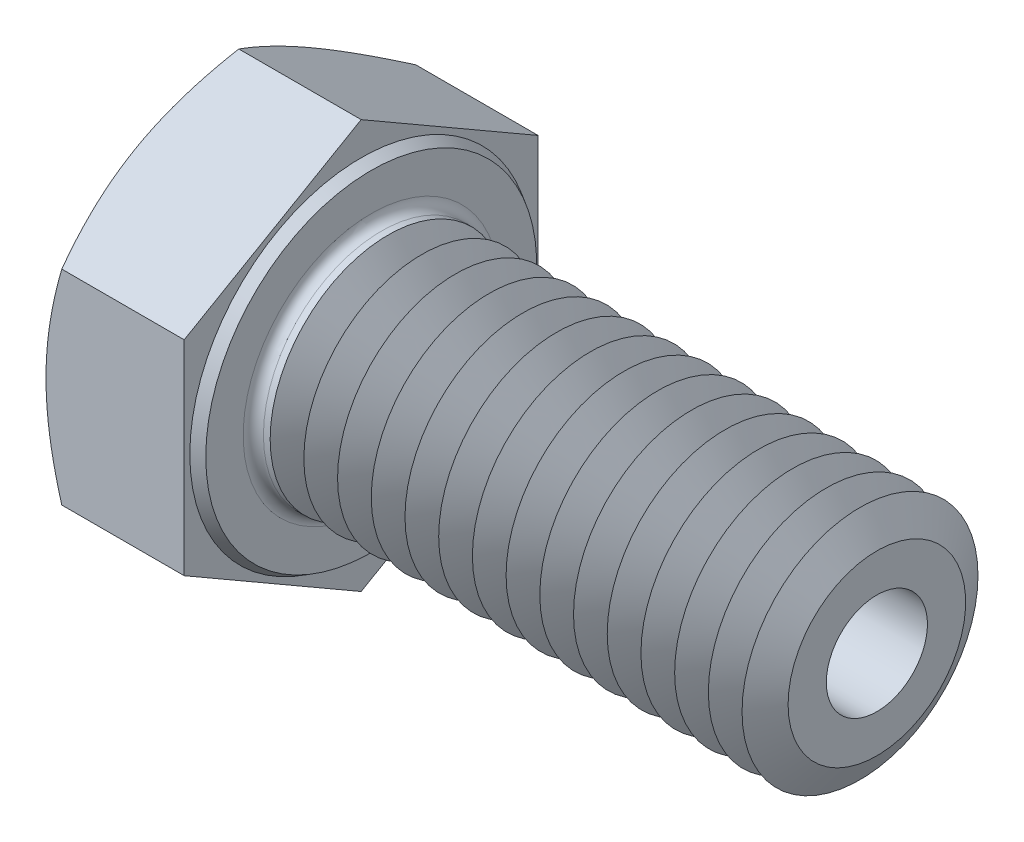
SolidWorks part; units mm, degrees
material "45"
ref_plane "前视" through (0, 0, 0) normal (0, 0, 1) x (1, 0, 0)
ref_plane "上视" through (0, 0, 0) normal (0, 1, 0) x (1, 0, 0)
ref_plane "右视" through (0, 0, 0) normal (1, 0, 0) x (0, 0, -1)
sketch "草图1" plane through (0, 0, 0) normal (1, 0, 0) x (0, 0, -1)
  line L0 (10.5, 6.0622) -> (10.5, -6.0622)
  line L1 (-10.5, 6.0622) -> (-10.5, -6.0622)
  line L2 (10.5, -6.0622) -> (0, -12.1244)
  line L3 (0, -12.1244) -> (-10.5, -6.0622)
  line L4 (10.5, 6.0622) -> (0, 12.1244)
  line L5 (0, 12.1244) -> (-10.5, 6.0622)
  circle A0 centre (0, 0) radius 11.68 construction
  dimension "e" = 23.36
  dimension "s" = 21
  dimension "D2" = 120
  dimension "D3" = 10.5
  dimension "D4" = 10.5
  dimension "D5" = 10.5
extrude "基体-拉伸" add sketch "草图1" along normal blind 8.8
sketch "草图2" plane through (0, 0, 0) normal (0, 0, 1) x (1, 0, 0)
  line L0 (0, 6.0622) -> (0, -6.0622) construction
  line L1 (0, 0) -> (38.8, 0)
  line L2 (0, 0) -> (0, 7)
  line L3 (0, 7) -> (38.8, 7)
  line L4 (38.8, 0) -> (38.8, 5.268)
  line L5 (8.8, 12.1244) -> (8.8, 6.0622) construction
  line L6 (0, 0) -> (-15.7, 0) construction
  line L7 (0, 0) -> (19.4, 0) construction
  line L8 (38.8, -5.268) -> (90.335, -7) construction
  line L9 (0, -7) -> (90.335, -7) construction
  line L10 (10.8, 7) -> (10.8, 0) construction
  line L11 (8.8, 13.0554) -> (8.8, -1.27) construction
  line L12 (8.8, 6.0622) -> (8.8, -6.0622) construction
  line L14 (38.8, 7) -> (38.8, 5.268)
  dimension "l" = 30
  dimension "d" = 14
  dimension "Minor_dia" = 10.536
  dimension "p" = 2
  dimension "b" = 30
  dimension "da" = 15.7
revolve "凸台-旋转1" add sketch "草图2" angle 360 about L7
cosmetic thread "螺旋线1" parameters "Thread_length"=27, "Thread_minor"=10.536
sketch "草图3" plane through (0, 0, 0) normal (0, 0, 1) x (1, 0, 0)
  line L0 (0, 10.5) -> (3.8246, 17.1244)
  line L1 (0, 12.1244) -> (0, 6.0622) construction
  line L2 (3.8246, 17.1244) -> (3.8246, 22.1244)
  line L3 (3.8246, 22.1244) -> (-10, 22.1244)
  line L4 (-10, 22.1244) -> (-10, 10.5)
  line L5 (-10, 10.5) -> (0, 10.5)
  line L6 (0, 0) -> (99.06, 0) construction
  line L7 (8.8, 12.1244) -> (0, 12.1244) construction
  dimension "D1" = 10.5
  dimension "D2" = 5
  dimension "D3" = 10
  dimension "D4" = 5
  dimension "Head_ch_ang" = 30
revolve "切除-旋转1" cut sketch "草图3" angle 360 about L6
sketch "草图4" plane through (0, 0, 0) normal (0, 0, 1) x (1, 0, 0)
  line L0 (0, 0) -> (248.9073, 0) construction
  line L2 (8.8, 0) -> (8.8, 9.82) construction
  line L3 (8.8, -7) -> (8.8, 7) construction
  line L4 (8.8, 12.1244) -> (8.8, 6.0622) construction
  line L9 (8.8, 9.82) -> (8.2, 10.1664)
  line L10 (8.2, 10.1664) -> (8.2, 12.1244)
  line L11 (8.8, 12.1244) -> (0.9378, 12.1244) construction
  line L12 (8.2, 12.1244) -> (8.8, 12.1244)
  line L13 (8.8, 12.1244) -> (8.8, 9.82)
  dimension "D1" = 120
  dimension "c" = 0.6
  dimension "dw" = 19.64
revolve "切除-旋转3" cut sketch "草图4" angle 360 about L0
fillet "圆角" radius 0.6 1 edges at (8.8, 0, -7)
sketch "草图6" plane through (0, 0, 0) normal (0, 0, 1) x (1, 0, 0)
  line L0 (0, 0) -> (38.8, 0) construction
  line L1 (38.8, -7) -> (38.8, 7) construction
  line L2 (38.8, 0) -> (38.8, 7) construction
  line L4 (37.8, 7) -> (39.8, 7)
  line L5 (37.8, 7) -> (38.8, 5.2679)
  line L6 (38.8, 5.2679) -> (39.8, 7)
  dimension "D1" = 2
revolve "切除-旋转4" cut sketch "草图6" angle 360 about L0
pattern_linear "阵列(线性)1" count 15 spacing 2 along (-1, 0, 0) of "切除-旋转4"
hole_wizard "Ø6.0 (6) 直径孔1" positions "3D草图1" profile "草图7" hole size "Ø6.0" standard "GB" end condition through all
sketch3d "3D草图1"
  arc A0 (0, 0, 10.5) -> (0, -9.0933, 5.25) centre (0, 0, 0) ccw construction
  point P0 (0, 0, 0)
  point P6 (10.5, 0, 0)
sketch "草图7" plane through (0, 0, 0) normal (0, 1, 0) x (0, 0, 1)
  line L0 (0, 0) -> (0, 38.8)
  line L1 (0, 38.8) -> (3, 38.8)
  line L2 (3, 38.8) -> (3, 0)
  line L5 (3, 0) -> (0, 0)
  line L11 (0, -6.35) -> (0, 107.95) construction
  dimension "通孔孔直径" = 6
  dimension "通孔孔深度" = 38.8
hole_wizard "M8x1.0 螺纹孔1" positions "3D草图2" profile "草图8" tap size "M8x1.0" standard "GB"
sketch3d "3D草图2"
  arc A0 (0, 0, 10.5) -> (0, -9.0933, 5.25) centre (0, 0, 0) ccw construction
  point P0 (0, 0, 0)
  point P6 (10.5, 0, 0)
sketch "草图8" plane through (0, 0, 0) normal (0, 1, 0) x (0, 0, 1)
  line L0 (0, 0) -> (0, 15.103)
  line L1 (0, 15.103) -> (3.5, 13)
  line L2 (3.5, 13) -> (3.5, 0)
  line L5 (3.5, 0) -> (0, 0)
  line L10 (0, 15.103) -> (-3.5, 13) construction
  line L11 (0, -6.35) -> (0, 107.95) construction
  dimension "螺纹孔钻头直径" = 7
  dimension "螺纹孔钻头深度" = 13
  dimension "导头角度" = 118
cosmetic thread "孔螺蚊线1" parameters "D1"=10, "D2"=8
